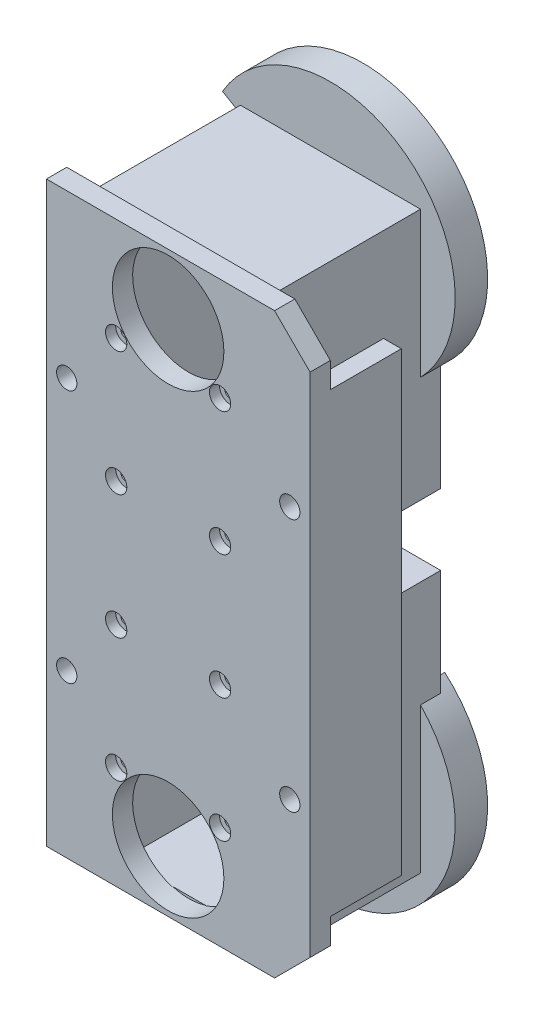
SolidWorks part; units mm, degrees
ref_plane "Front Plane" through (0, 0, 0) normal (0, 0, 1) x (1, 0, 0)
ref_plane "Top Plane" through (0, 0, 0) normal (0, 1, 0) x (1, 0, 0)
ref_plane "Right Plane" through (0, 0, 0) normal (1, 0, 0) x (0, 0, -1)
ref_plane "PZ_p64_625" through (0, 0, 64.625) normal (0, 0, 1) x (1, 0, 0)
sketch "S_prism1" plane through (0, 0, 64.625) normal (0, 0, 1) x (1, 0, 0)
  line L0 (28, -50) -> (28, 50)
  line L1 (28, 50) -> (21, 57)
  line L2 (21, 57) -> (-24, 57)
  line L3 (-24, 57) -> (-24, -57)
  line L4 (-24, -57) -> (21, -57)
  line L5 (21, -57) -> (28, -50)
extrude "Boss_1" add sketch "S_prism1" along normal blind 4
ref_plane "PZ_p50_625" through (0, 0, 50.625) normal (0, 0, 1) x (1, 0, 0)
sketch "S_box2" plane through (0, 0, 50.625) normal (0, 0, 1) x (1, 0, 0)
  line L0 (24.5, -45) -> (28, -45)
  line L1 (28, -45) -> (28, 45)
  line L2 (28, 45) -> (24.5, 45)
  line L3 (24.5, 45) -> (24.5, -45)
  dimension "P1" = 24.5
  dimension "P2" = 45
  dimension "P3" = 28
  dimension "P4" = 45
  dimension "P5" = 28
  dimension "P6" = 45
  dimension "P7" = 24.5
  dimension "P8" = 45
extrude "Boss_2" add sketch "S_box2" along normal blind 14.5
sketch "S_box3" plane through (0, 0, 50.625) normal (0, 0, 1) x (1, 0, 0)
  line L0 (-24, -45) -> (-20.5, -45)
  line L1 (-20.5, -45) -> (-20.5, 45)
  line L2 (-20.5, 45) -> (-24, 45)
  line L3 (-24, 45) -> (-24, -45)
  dimension "P1" = 24
  dimension "P2" = 45
  dimension "P3" = 20.5
  dimension "P4" = 45
  dimension "P5" = 20.5
  dimension "P6" = 45
  dimension "P7" = 24
  dimension "P8" = 45
extrude "Boss_3" add sketch "S_box3" along normal blind 14.5
ref_plane "PZ_p32_625" through (0, 0, 32.625) normal (0, 0, 1) x (1, 0, 0)
sketch "S_box4" plane through (0, 0, 32.625) normal (0, 0, 1) x (1, 0, 0)
  line L0 (-17.76, 6.99) -> (17.76, 6.99)
  line L1 (17.76, 6.99) -> (17.76, 9.49)
  line L2 (17.76, 9.49) -> (-17.76, 9.49)
  line L3 (-17.76, 9.49) -> (-17.76, 6.99)
  dimension "P1" = 17.76
  dimension "P2" = 6.99
  dimension "P3" = 17.76
  dimension "P4" = 6.99
  dimension "P5" = 17.76
  dimension "P6" = 9.49
  dimension "P7" = 17.76
  dimension "P8" = 9.49
extrude "Boss_4" add sketch "S_box4" along normal blind 36
sketch "S_box5" plane through (0, 0, 32.625) normal (0, 0, 1) x (1, 0, 0)
  line L0 (-17.76, 55.51) -> (17.76, 55.51)
  line L1 (17.76, 55.51) -> (17.76, 56.71)
  line L2 (17.76, 56.71) -> (-17.76, 56.71)
  line L3 (-17.76, 56.71) -> (-17.76, 55.51)
  dimension "P1" = 17.76
  dimension "P2" = 55.51
  dimension "P3" = 17.76
  dimension "P4" = 55.51
  dimension "P5" = 17.76
  dimension "P6" = 56.71
  dimension "P7" = 17.76
  dimension "P8" = 56.71
extrude "Boss_5" add sketch "S_box5" along normal blind 36
sketch "S_box6" plane through (0, 0, 32.625) normal (0, 0, 1) x (1, 0, 0)
  line L0 (-17.76, 6.99) -> (-12.76, 6.99)
  line L1 (-12.76, 6.99) -> (-12.76, 56.71)
  line L2 (-12.76, 56.71) -> (-17.76, 56.71)
  line L3 (-17.76, 56.71) -> (-17.76, 6.99)
  dimension "P1" = 17.76
  dimension "P2" = 6.99
  dimension "P3" = 12.76
  dimension "P4" = 6.99
  dimension "P5" = 12.76
  dimension "P6" = 56.71
  dimension "P7" = 17.76
  dimension "P8" = 56.71
extrude "Boss_6" add sketch "S_box6" along normal blind 36
sketch "S_box7" plane through (0, 0, 32.625) normal (0, 0, 1) x (1, 0, 0)
  line L0 (12.76, 6.99) -> (17.76, 6.99)
  line L1 (17.76, 6.99) -> (17.76, 56.71)
  line L2 (17.76, 56.71) -> (12.76, 56.71)
  line L3 (12.76, 56.71) -> (12.76, 6.99)
  dimension "P1" = 12.76
  dimension "P2" = 6.99
  dimension "P3" = 17.76
  dimension "P4" = 6.99
  dimension "P5" = 17.76
  dimension "P6" = 56.71
  dimension "P7" = 12.76
  dimension "P8" = 56.71
extrude "Boss_7" add sketch "S_box7" along normal blind 36
sketch "S_box8" plane through (0, 0, 64.625) normal (0, 0, 1) x (1, 0, 0)
  line L0 (-17.76, 6.99) -> (17.76, 6.99)
  line L1 (17.76, 6.99) -> (17.76, 56.71)
  line L2 (17.76, 56.71) -> (-17.76, 56.71)
  line L3 (-17.76, 56.71) -> (-17.76, 6.99)
  dimension "P1" = 17.76
  dimension "P2" = 6.99
  dimension "P3" = 17.76
  dimension "P4" = 6.99
  dimension "P5" = 17.76
  dimension "P6" = 56.71
  dimension "P7" = 17.76
  dimension "P8" = 56.71
extrude "Boss_8" add sketch "S_box8" along normal blind 4
ref_plane "PZ_p30_100" through (0, 0, 30.1) normal (0, 0, 1) x (1, 0, 0)
sketch "S_cyl9" plane through (0, 0, 30.1) normal (0, 0, 1) x (1, 0, 0)
  circle A0 centre (0, 45) radius 19
  dimension "D1_S_cyl9" = 38
  dimension "P2" = 45
extrude "Boss_9" add sketch "S_cyl9" along normal blind 2.525
ref_plane "PZ_p30_200" through (0, 0, 30.2) normal (0, 0, 1) x (1, 0, 0)
sketch "S_prism10" plane through (0, 0, 30.2) normal (0, 0, 1) x (1, 0, 0)
  line L0 (-21.3042, 57.3) -> (-9.5263, 50.5)
  line L1 (7.2166, 36.6982) -> (16.1391, 26.4341)
  arc A0 (16.1391, 26.4341) -> (-21.3042, 57.3) centre (0, 45) ccw
  arc A1 (-9.5263, 50.5) -> (7.2166, 36.6982) centre (0, 45) cw
extrude "Boss_10" add sketch "S_prism10" along normal blind 6.4
sketch "S_box11" plane through (0, 0, 32.625) normal (0, 0, 1) x (1, 0, 0)
  line L0 (-17.76, -56.71) -> (17.76, -56.71)
  line L1 (17.76, -56.71) -> (17.76, -55.51)
  line L2 (17.76, -55.51) -> (-17.76, -55.51)
  line L3 (-17.76, -55.51) -> (-17.76, -56.71)
  dimension "P1" = 17.76
  dimension "P2" = 56.71
  dimension "P3" = 17.76
  dimension "P4" = 56.71
  dimension "P5" = 17.76
  dimension "P6" = 55.51
  dimension "P7" = 17.76
  dimension "P8" = 55.51
extrude "Boss_11" add sketch "S_box11" along normal blind 36
sketch "S_box12" plane through (0, 0, 32.625) normal (0, 0, 1) x (1, 0, 0)
  line L0 (-17.76, -9.49) -> (17.76, -9.49)
  line L1 (17.76, -9.49) -> (17.76, -6.99)
  line L2 (17.76, -6.99) -> (-17.76, -6.99)
  line L3 (-17.76, -6.99) -> (-17.76, -9.49)
  dimension "P1" = 17.76
  dimension "P2" = 9.49
  dimension "P3" = 17.76
  dimension "P4" = 9.49
  dimension "P5" = 17.76
  dimension "P6" = 6.99
  dimension "P7" = 17.76
  dimension "P8" = 6.99
extrude "Boss_12" add sketch "S_box12" along normal blind 36
sketch "S_box13" plane through (0, 0, 32.625) normal (0, 0, 1) x (1, 0, 0)
  line L0 (-17.76, -56.71) -> (-12.76, -56.71)
  line L1 (-12.76, -56.71) -> (-12.76, -6.99)
  line L2 (-12.76, -6.99) -> (-17.76, -6.99)
  line L3 (-17.76, -6.99) -> (-17.76, -56.71)
  dimension "P1" = 17.76
  dimension "P2" = 56.71
  dimension "P3" = 12.76
  dimension "P4" = 56.71
  dimension "P5" = 12.76
  dimension "P6" = 6.99
  dimension "P7" = 17.76
  dimension "P8" = 6.99
extrude "Boss_13" add sketch "S_box13" along normal blind 36
sketch "S_box14" plane through (0, 0, 32.625) normal (0, 0, 1) x (1, 0, 0)
  line L0 (12.76, -56.71) -> (17.76, -56.71)
  line L1 (17.76, -56.71) -> (17.76, -6.99)
  line L2 (17.76, -6.99) -> (12.76, -6.99)
  line L3 (12.76, -6.99) -> (12.76, -56.71)
  dimension "P1" = 12.76
  dimension "P2" = 56.71
  dimension "P3" = 17.76
  dimension "P4" = 56.71
  dimension "P5" = 17.76
  dimension "P6" = 6.99
  dimension "P7" = 12.76
  dimension "P8" = 6.99
extrude "Boss_14" add sketch "S_box14" along normal blind 36
sketch "S_box15" plane through (0, 0, 64.625) normal (0, 0, 1) x (1, 0, 0)
  line L0 (-17.76, -56.71) -> (17.76, -56.71)
  line L1 (17.76, -56.71) -> (17.76, -6.99)
  line L2 (17.76, -6.99) -> (-17.76, -6.99)
  line L3 (-17.76, -6.99) -> (-17.76, -56.71)
  dimension "P1" = 17.76
  dimension "P2" = 56.71
  dimension "P3" = 17.76
  dimension "P4" = 56.71
  dimension "P5" = 17.76
  dimension "P6" = 6.99
  dimension "P7" = 17.76
  dimension "P8" = 6.99
extrude "Boss_15" add sketch "S_box15" along normal blind 4
sketch "S_cyl16" plane through (0, 0, 30.1) normal (0, 0, 1) x (1, 0, 0)
  circle A0 centre (0, -45) radius 19
  dimension "D1_S_cyl16" = 38
  dimension "P2" = 45
extrude "Boss_16" add sketch "S_cyl16" along normal blind 2.525
sketch "S_prism17" plane through (0, 0, 30.2) normal (0, 0, 1) x (1, 0, 0)
  line L0 (16.1391, -26.4341) -> (7.2166, -36.6982)
  line L1 (-9.5263, -50.5) -> (-21.3042, -57.3)
  arc A0 (-21.3042, -57.3) -> (16.1391, -26.4341) centre (0, -45) ccw
  arc A1 (7.2166, -36.6982) -> (-9.5263, -50.5) centre (0, -45) cw
extrude "Boss_17" add sketch "S_prism17" along normal blind 6.4
ref_plane "PZ_p64_525" through (0, 0, 64.525) normal (0, 0, 1) x (1, 0, 0)
sketch "S_hole18" plane through (0, 0, 64.525) normal (0, 0, 1) x (1, 0, 0)
  circle A0 centre (0, 45) radius 11
  dimension "D1_S_hole18" = 22
  dimension "P2" = 45
extrude "Hole_18" cut sketch "S_hole18" along normal blind 4.2
sketch "S_hole19" plane through (0, 0, 64.525) normal (0, 0, 1) x (1, 0, 0)
  circle A0 centre (-10.25, 36.7) radius 1.1
  dimension "D1_S_hole19" = 2.2
  dimension "P2" = 10.25
  dimension "P3" = 36.7
extrude "Hole_19" cut sketch "S_hole19" along normal blind 4.2
ref_plane "PZ_p66_625" through (0, 0, 66.625) normal (0, 0, 1) x (1, 0, 0)
sketch "S_hole20" plane through (0, 0, 66.625) normal (0, 0, 1) x (1, 0, 0)
  circle A0 centre (-10.25, 36.7) radius 2.1
  dimension "D1_S_hole20" = 4.2
  dimension "P2" = 10.25
  dimension "P3" = 36.7
extrude "Hole_20" cut sketch "S_hole20" along normal blind 2.1
sketch "S_hole21" plane through (0, 0, 64.525) normal (0, 0, 1) x (1, 0, 0)
  circle A0 centre (10.25, 36.7) radius 1.1
  dimension "D1_S_hole21" = 2.2
  dimension "P2" = 10.25
  dimension "P3" = 36.7
extrude "Hole_21" cut sketch "S_hole21" along normal blind 4.2
sketch "S_hole22" plane through (0, 0, 66.625) normal (0, 0, 1) x (1, 0, 0)
  circle A0 centre (10.25, 36.7) radius 2.1
  dimension "D1_S_hole22" = 4.2
  dimension "P2" = 10.25
  dimension "P3" = 36.7
extrude "Hole_22" cut sketch "S_hole22" along normal blind 2.1
sketch "S_hole23" plane through (0, 0, 64.525) normal (0, 0, 1) x (1, 0, 0)
  circle A0 centre (-10.25, 12.25) radius 1.1
  dimension "D1_S_hole23" = 2.2
  dimension "P2" = 10.25
  dimension "P3" = 12.25
extrude "Hole_23" cut sketch "S_hole23" along normal blind 4.2
sketch "S_hole24" plane through (0, 0, 66.625) normal (0, 0, 1) x (1, 0, 0)
  circle A0 centre (-10.25, 12.25) radius 2.1
  dimension "D1_S_hole24" = 4.2
  dimension "P2" = 10.25
  dimension "P3" = 12.25
extrude "Hole_24" cut sketch "S_hole24" along normal blind 2.1
sketch "S_hole25" plane through (0, 0, 64.525) normal (0, 0, 1) x (1, 0, 0)
  circle A0 centre (10.25, 12.25) radius 1.1
  dimension "D1_S_hole25" = 2.2
  dimension "P2" = 10.25
  dimension "P3" = 12.25
extrude "Hole_25" cut sketch "S_hole25" along normal blind 4.2
sketch "S_hole26" plane through (0, 0, 66.625) normal (0, 0, 1) x (1, 0, 0)
  circle A0 centre (10.25, 12.25) radius 2.1
  dimension "D1_S_hole26" = 4.2
  dimension "P2" = 10.25
  dimension "P3" = 12.25
extrude "Hole_26" cut sketch "S_hole26" along normal blind 2.1
sketch "S_cut27" plane through (0, 0, 32.625) normal (0, 0, 1) x (1, 0, 0)
  line L0 (-12.76, 9.49) -> (12.76, 9.49)
  line L1 (12.76, 9.49) -> (12.76, 55.51)
  line L2 (12.76, 55.51) -> (-12.76, 55.51)
  line L3 (-12.76, 55.51) -> (-12.76, 9.49)
  dimension "P1" = 12.76
  dimension "P2" = 9.49
  dimension "P3" = 12.76
  dimension "P4" = 9.49
  dimension "P5" = 12.76
  dimension "P6" = 55.51
  dimension "P7" = 12.76
  dimension "P8" = 55.51
extrude "Pocket_27" cut sketch "S_cut27" along normal blind 4.075
sketch "S_hole28" plane through (0, 0, 30.1) normal (0, 0, 1) x (1, 0, 0)
  circle A0 centre (0, 45) radius 11.5
  dimension "D1_S_hole28" = 23
  dimension "P2" = 45
extrude "Hole_28" cut sketch "S_hole28" along normal blind 2.625
sketch "S_hole29" plane through (0, 0, 30.1) normal (0, 0, 1) x (1, 0, 0)
  circle A0 centre (19.9388, 35.7024) radius 0.9
  dimension "D1_S_hole29" = 1.8
  dimension "P2" = 19.9388
  dimension "P3" = 35.7024
extrude "Hole_29" cut sketch "S_hole29" along normal blind 5.7
sketch "S_hole30" plane through (0, 0, 30.1) normal (0, 0, 1) x (1, 0, 0)
  circle A0 centre (21.2504, 50.694) radius 0.9
  dimension "D1_S_hole30" = 1.8
  dimension "P2" = 21.2504
  dimension "P3" = 50.694
extrude "Hole_30" cut sketch "S_hole30" along normal blind 5.7
sketch "S_hole31" plane through (0, 0, 30.1) normal (0, 0, 1) x (1, 0, 0)
  circle A0 centre (12.6187, 63.0213) radius 0.9
  dimension "D1_S_hole31" = 1.8
  dimension "P2" = 12.6187
  dimension "P3" = 63.0213
extrude "Hole_31" cut sketch "S_hole31" along normal blind 5.7
sketch "S_hole32" plane through (0, 0, 30.1) normal (0, 0, 1) x (1, 0, 0)
  circle A0 centre (0.7678, 66.9866) radius 0.9
  dimension "D1_S_hole32" = 1.8
  dimension "P2" = 0.7678
  dimension "P3" = 66.9866
extrude "Hole_32" cut sketch "S_hole32" along normal blind 5.7
sketch "S_hole33" plane through (0, 0, 64.525) normal (0, 0, 1) x (1, 0, 0)
  circle A0 centre (0, -45) radius 11
  dimension "D1_S_hole33" = 22
  dimension "P2" = 45
extrude "Hole_33" cut sketch "S_hole33" along normal blind 4.2
sketch "S_hole34" plane through (0, 0, 64.525) normal (0, 0, 1) x (1, 0, 0)
  circle A0 centre (-10.25, -36.7) radius 1.1
  dimension "D1_S_hole34" = 2.2
  dimension "P2" = 10.25
  dimension "P3" = 36.7
extrude "Hole_34" cut sketch "S_hole34" along normal blind 4.2
sketch "S_hole35" plane through (0, 0, 66.625) normal (0, 0, 1) x (1, 0, 0)
  circle A0 centre (-10.25, -36.7) radius 2.1
  dimension "D1_S_hole35" = 4.2
  dimension "P2" = 10.25
  dimension "P3" = 36.7
extrude "Hole_35" cut sketch "S_hole35" along normal blind 2.1
sketch "S_hole36" plane through (0, 0, 64.525) normal (0, 0, 1) x (1, 0, 0)
  circle A0 centre (10.25, -36.7) radius 1.1
  dimension "D1_S_hole36" = 2.2
  dimension "P2" = 10.25
  dimension "P3" = 36.7
extrude "Hole_36" cut sketch "S_hole36" along normal blind 4.2
sketch "S_hole37" plane through (0, 0, 66.625) normal (0, 0, 1) x (1, 0, 0)
  circle A0 centre (10.25, -36.7) radius 2.1
  dimension "D1_S_hole37" = 4.2
  dimension "P2" = 10.25
  dimension "P3" = 36.7
extrude "Hole_37" cut sketch "S_hole37" along normal blind 2.1
sketch "S_hole38" plane through (0, 0, 64.525) normal (0, 0, 1) x (1, 0, 0)
  circle A0 centre (-10.25, -12.25) radius 1.1
  dimension "D1_S_hole38" = 2.2
  dimension "P2" = 10.25
  dimension "P3" = 12.25
extrude "Hole_38" cut sketch "S_hole38" along normal blind 4.2
sketch "S_hole39" plane through (0, 0, 66.625) normal (0, 0, 1) x (1, 0, 0)
  circle A0 centre (-10.25, -12.25) radius 2.1
  dimension "D1_S_hole39" = 4.2
  dimension "P2" = 10.25
  dimension "P3" = 12.25
extrude "Hole_39" cut sketch "S_hole39" along normal blind 2.1
sketch "S_hole40" plane through (0, 0, 64.525) normal (0, 0, 1) x (1, 0, 0)
  circle A0 centre (10.25, -12.25) radius 1.1
  dimension "D1_S_hole40" = 2.2
  dimension "P2" = 10.25
  dimension "P3" = 12.25
extrude "Hole_40" cut sketch "S_hole40" along normal blind 4.2
sketch "S_hole41" plane through (0, 0, 66.625) normal (0, 0, 1) x (1, 0, 0)
  circle A0 centre (10.25, -12.25) radius 2.1
  dimension "D1_S_hole41" = 4.2
  dimension "P2" = 10.25
  dimension "P3" = 12.25
extrude "Hole_41" cut sketch "S_hole41" along normal blind 2.1
sketch "S_cut42" plane through (0, 0, 32.625) normal (0, 0, 1) x (1, 0, 0)
  line L0 (-12.76, -55.51) -> (12.76, -55.51)
  line L1 (12.76, -55.51) -> (12.76, -9.49)
  line L2 (12.76, -9.49) -> (-12.76, -9.49)
  line L3 (-12.76, -9.49) -> (-12.76, -55.51)
  dimension "P1" = 12.76
  dimension "P2" = 55.51
  dimension "P3" = 12.76
  dimension "P4" = 55.51
  dimension "P5" = 12.76
  dimension "P6" = 9.49
  dimension "P7" = 12.76
  dimension "P8" = 9.49
extrude "Pocket_42" cut sketch "S_cut42" along normal blind 4.075
sketch "S_hole43" plane through (0, 0, 30.1) normal (0, 0, 1) x (1, 0, 0)
  circle A0 centre (0, -45) radius 11.5
  dimension "D1_S_hole43" = 23
  dimension "P2" = 45
extrude "Hole_43" cut sketch "S_hole43" along normal blind 2.625
sketch "S_hole44" plane through (0, 0, 30.1) normal (0, 0, 1) x (1, 0, 0)
  circle A0 centre (19.9388, -35.7024) radius 0.9
  dimension "D1_S_hole44" = 1.8
  dimension "P2" = 19.9388
  dimension "P3" = 35.7024
extrude "Hole_44" cut sketch "S_hole44" along normal blind 5.7
sketch "S_hole45" plane through (0, 0, 30.1) normal (0, 0, 1) x (1, 0, 0)
  circle A0 centre (21.2504, -50.694) radius 0.9
  dimension "D1_S_hole45" = 1.8
  dimension "P2" = 21.2504
  dimension "P3" = 50.694
extrude "Hole_45" cut sketch "S_hole45" along normal blind 5.7
sketch "S_hole46" plane through (0, 0, 30.1) normal (0, 0, 1) x (1, 0, 0)
  circle A0 centre (12.6187, -63.0213) radius 0.9
  dimension "D1_S_hole46" = 1.8
  dimension "P2" = 12.6187
  dimension "P3" = 63.0213
extrude "Hole_46" cut sketch "S_hole46" along normal blind 5.7
sketch "S_hole47" plane through (0, 0, 30.1) normal (0, 0, 1) x (1, 0, 0)
  circle A0 centre (0.7678, -66.9866) radius 0.9
  dimension "D1_S_hole47" = 1.8
  dimension "P2" = 0.7678
  dimension "P3" = 66.9866
extrude "Hole_47" cut sketch "S_hole47" along normal blind 5.7
sketch "S_hole48" plane through (0, 0, 64.525) normal (0, 0, 1) x (1, 0, 0)
  circle A0 centre (-20, -25) radius 2
  dimension "D1_S_hole48" = 4
  dimension "P2" = 20
  dimension "P3" = 25
extrude "Hole_48" cut sketch "S_hole48" along normal blind 4.2
sketch "S_hole49" plane through (0, 0, 64.525) normal (0, 0, 1) x (1, 0, 0)
  circle A0 centre (-20, 25) radius 2
  dimension "D1_S_hole49" = 4
  dimension "P2" = 20
  dimension "P3" = 25
extrude "Hole_49" cut sketch "S_hole49" along normal blind 4.2
sketch "S_hole50" plane through (0, 0, 64.525) normal (0, 0, 1) x (1, 0, 0)
  circle A0 centre (24, -25) radius 2
  dimension "D1_S_hole50" = 4
  dimension "P2" = 24
  dimension "P3" = 25
extrude "Hole_50" cut sketch "S_hole50" along normal blind 4.2
sketch "S_hole51" plane through (0, 0, 64.525) normal (0, 0, 1) x (1, 0, 0)
  circle A0 centre (24, 25) radius 2
  dimension "D1_S_hole51" = 4
  dimension "P2" = 24
  dimension "P3" = 25
extrude "Hole_51" cut sketch "S_hole51" along normal blind 4.2
equation "\"plate_t\" = 3"
equation "\"clearance\" = 0.4"
